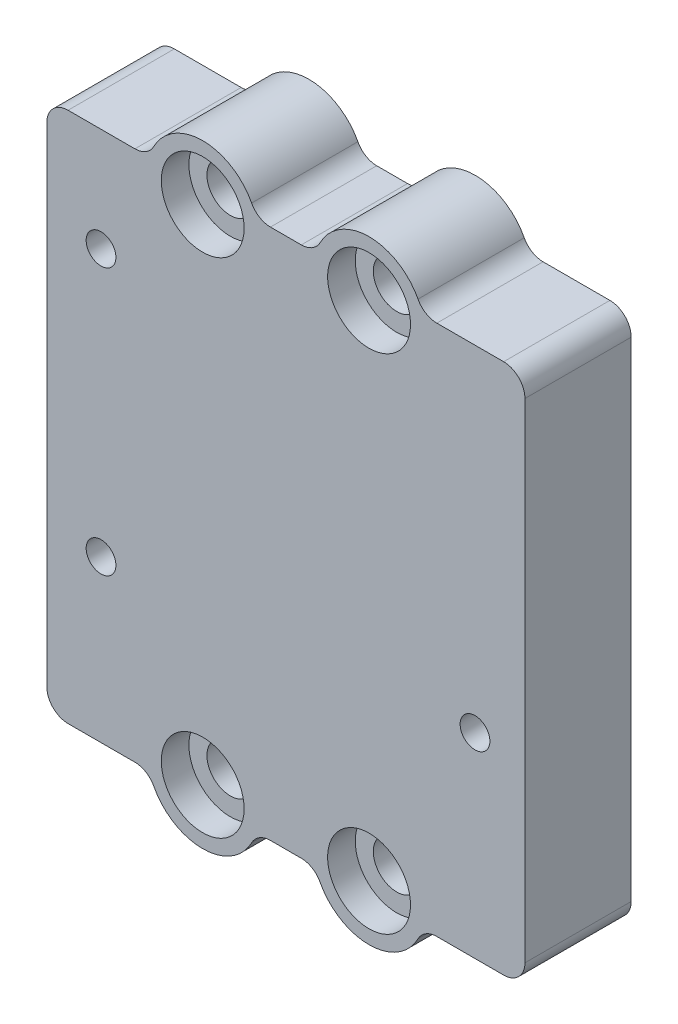
SolidWorks part; units mm, degrees
ref_plane "Front Plane" through (0, 0, 0) normal (0, 0, 1) x (1, 0, 0)
ref_plane "Top Plane" through (0, 0, 0) normal (0, 1, 0) x (1, 0, 0)
ref_plane "Right Plane" through (0, 0, 0) normal (1, 0, 0) x (0, 0, -1)
sketch "Sketch1" plane through (0, 0, 0) normal (0, 0, 1) x (1, 0, 0)
  line L1 (9.9441, -30.0482) -> (-9.9441, -30.0482) construction
  line L2 (9.9441, -30.0482) -> (9.9441, 30.0482) construction
  line L3 (9.9441, 30.0482) -> (-9.9441, 30.0482) construction
  line L4 (-9.9441, -30.0482) -> (-9.9441, 30.0482) construction
  line L5 (9.9441, -30.0482) -> (-9.9441, 30.0482) construction
  line L6 (9.9441, 30.0482) -> (-9.9441, -30.0482) construction
  line L7 (26.035, 31.75) -> (-26.035, 31.75)
  line L8 (28.575, 29.21) -> (28.575, -29.21)
  line L9 (26.035, -31.75) -> (-26.035, -31.75)
  line L10 (-28.575, 29.21) -> (-28.575, -29.21)
  line L11 (28.575, 31.75) -> (-28.575, -31.75) construction
  line L12 (28.575, -31.75) -> (-28.575, 31.75) construction
  circle A0 centre (-9.9441, 30.0482) radius 2.1082 construction
  circle A1 centre (9.9441, 30.0482) radius 2.1082 construction
  circle A2 centre (9.9441, -30.0482) radius 2.1082 construction
  circle A3 centre (-9.9441, -30.0482) radius 2.1082 construction
  circle A4 centre (-9.9441, 30.0482) radius 2.794
  circle A5 centre (9.9441, 30.0482) radius 2.794
  circle A6 centre (9.9441, -30.0482) radius 2.794
  circle A7 centre (-9.9441, -30.0482) radius 2.794
  circle A8 centre (-9.9441, 30.0482) radius 6.604
  circle A9 centre (9.9441, 30.0482) radius 6.604
  circle A10 centre (9.9441, -30.0482) radius 6.604
  circle A11 centre (-9.9441, -30.0482) radius 6.604
  arc A12 (-26.035, -31.75) -> (-28.575, -29.21) centre (-26.035, -29.21) cw
  arc A13 (28.575, -29.21) -> (26.035, -31.75) centre (26.035, -29.21) cw
  arc A14 (26.035, 31.75) -> (28.575, 29.21) centre (26.035, 29.21) cw
  arc A15 (-26.035, 31.75) -> (-28.575, 29.21) centre (-26.035, 29.21) ccw
  point P0 (0, 0)
  point P22 (0, 0)
  dimension "D1" = 4.2164
  dimension "D2" = 15.6718
  dimension "D3" = 55.88
  dimension "D4" = 5.588
  dimension "D8" = 2.54
  dimension "D6" = 57.15
  dimension "D7" = 63.5
  dimension "D5" = 3.81
extrude "Boss-Extrude1" add sketch "Sketch1" along normal blind 12.7 contours L7 A15 L10 A12 L9 A11 A10 A13 L8 A14 A9 A8 | L9 A11 A7 | L9 A11 A7 | L9 A10 A6 | L9 A10 A6 | L7 A9 A5 | L7 A9 A5 | L7 A8 A4 | L7 A8 A4
sketch "Sketch2" plane through (0, 0, 12.7) normal (0, 0, 1) x (1, 0, 0)
  line L1 (26.416, 27.6225) -> (-26.416, 27.6225)
  line L2 (26.416, 27.6225) -> (26.416, -27.6225)
  line L3 (26.416, -27.6225) -> (-26.416, -27.6225)
  line L4 (-26.416, 27.6225) -> (-26.416, -27.6225)
  line L5 (26.416, 27.6225) -> (-26.416, -27.6225) construction
  line L6 (26.416, -27.6225) -> (-26.416, 27.6225) construction
  circle A0 centre (-22.098, -12.5095) radius 1.778
  circle A1 centre (22.606, -8.3693) radius 1.778
  circle A2 centre (-22.098, 19.3675) radius 1.778
  point P4 (0, 0)
  dimension "D2" = 2.54
  dimension "D3" = 28.321
  dimension "D4" = 2.032
  dimension "D6" = 17.4752
  dimension "D7" = 3.556
  dimension "D8" = 13.335
  dimension "D1" = 52.832
  dimension "D5" = 55.245
extrude "Cut-Extrude1" cut sketch "Sketch2" against normal through all contours A2 | A0 | A1
sketch "Sketch3" plane through (0, 0, 0) normal (0, 0, -1) x (-1, 0, 0)
  line L1 (-22.606, -12.4754) -> (-19.05, -10.4224)
  line L2 (-19.05, -10.4224) -> (-19.05, -6.3162)
  line L3 (-19.05, -6.3162) -> (-22.606, -4.2632)
  line L4 (-22.606, -4.2632) -> (-26.162, -6.3162)
  line L5 (-26.162, -6.3162) -> (-26.162, -10.4224)
  line L6 (-26.162, -10.4224) -> (-22.606, -12.4754)
  line L7 (22.098, -16.6156) -> (25.654, -14.5626)
  line L8 (25.654, -14.5626) -> (25.654, -10.4564)
  line L9 (25.654, -10.4564) -> (22.098, -8.4034)
  line L10 (22.098, -8.4034) -> (18.542, -10.4564)
  line L11 (18.542, -10.4564) -> (18.542, -14.5626)
  line L12 (18.542, -14.5626) -> (22.098, -16.6156)
  line L13 (22.098, 15.2614) -> (25.654, 17.3144)
  line L14 (25.654, 17.3144) -> (25.654, 21.4206)
  line L15 (25.654, 21.4206) -> (22.098, 23.4736)
  line L16 (22.098, 23.4736) -> (18.542, 21.4206)
  line L17 (18.542, 21.4206) -> (18.542, 17.3144)
  line L18 (18.542, 17.3144) -> (22.098, 15.2614)
  circle A0 centre (-22.606, -8.3693) radius 3.556 construction
  circle A1 centre (22.098, -12.5095) radius 3.556 construction
  circle A2 centre (22.098, 19.3675) radius 3.556 construction
  dimension "D1" = 7.112
sketch "Sketch4" plane through (0, 0, 12.7) normal (0, 0, 1) x (1, 0, 0)
  circle A0 centre (-9.9441, 30.0482) radius 4.953
  circle A1 centre (9.9441, 30.0482) radius 4.953
  circle A2 centre (-9.9441, -30.0482) radius 4.953
  circle A3 centre (9.9441, -30.0482) radius 4.953
  dimension "D1" = 9.906
extrude "Cut-Extrude3" cut sketch "Sketch4" against normal blind 3.302
fillet "Fillet1" radius 2.54 8 edges at (-3.5631, -31.75, 6.35) (-16.3251, -31.75, 6.35) (16.3251, -31.75, 6.35) (3.5631, -31.75, 6.35) (3.5631, 31.75, 6.35) (16.3251, 31.75, 6.35) (-16.3251, 31.75, 6.35) (-3.5631, 31.75, 6.35)
extrude "Cut-Extrude4" cut sketch "Sketch3" against normal blind 3.302
